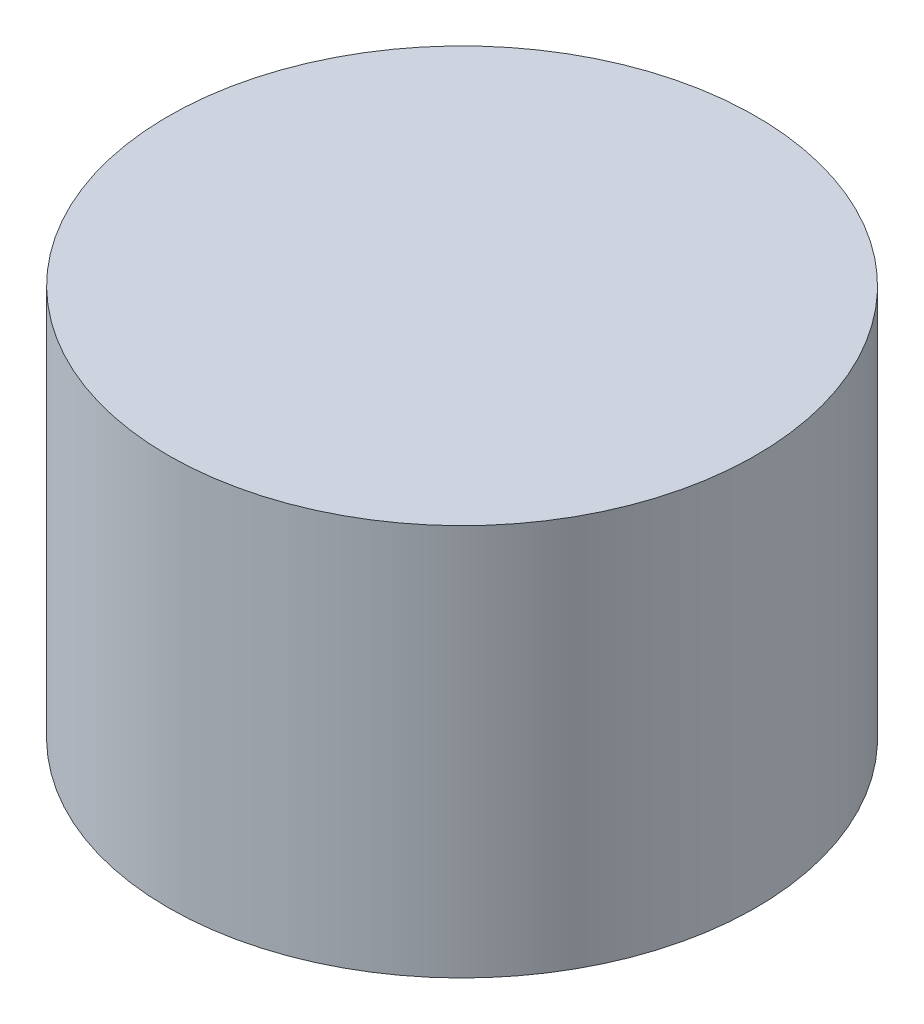
SolidWorks part; units mm, degrees
ref_plane "Front Plane" through (0, 0, 0) normal (0, 0, 1) x (1, 0, 0)
ref_plane "Top Plane" through (0, 0, 0) normal (0, 1, 0) x (1, 0, 0)
ref_plane "Right Plane" through (0, 0, 0) normal (1, 0, 0) x (0, 0, -1)
sketch "Sketch1" plane through (0, 0, 0) normal (0, 1, 0) x (1, 0, 0)
  circle A0 centre (0, 0) radius 24
extrude "Boss-Extrude1" add sketch "Sketch1" along normal blind 32
